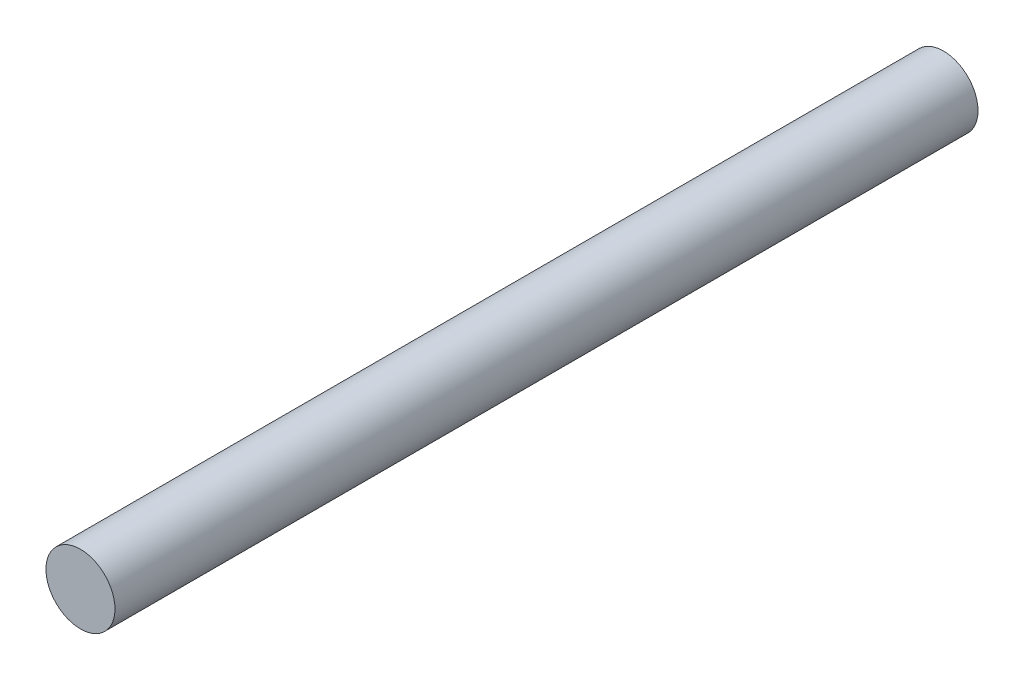
SolidWorks part; units mm, degrees
ref_plane "Front Plane" through (0, 0, 0) normal (0, 0, 1) x (1, 0, 0)
ref_plane "Top Plane" through (0, 0, 0) normal (0, 1, 0) x (1, 0, 0)
ref_plane "Right Plane" through (0, 0, 0) normal (1, 0, 0) x (0, 0, -1)
sketch "Sketch1" plane through (0, 0, 0) normal (0, 0, 1) x (1, 0, 0)
  circle A0 centre (0, 0) radius 1.6
  dimension "D1" = 3.2
extrude "Boss-Extrude1" add sketch "Sketch1" along normal blind 40
